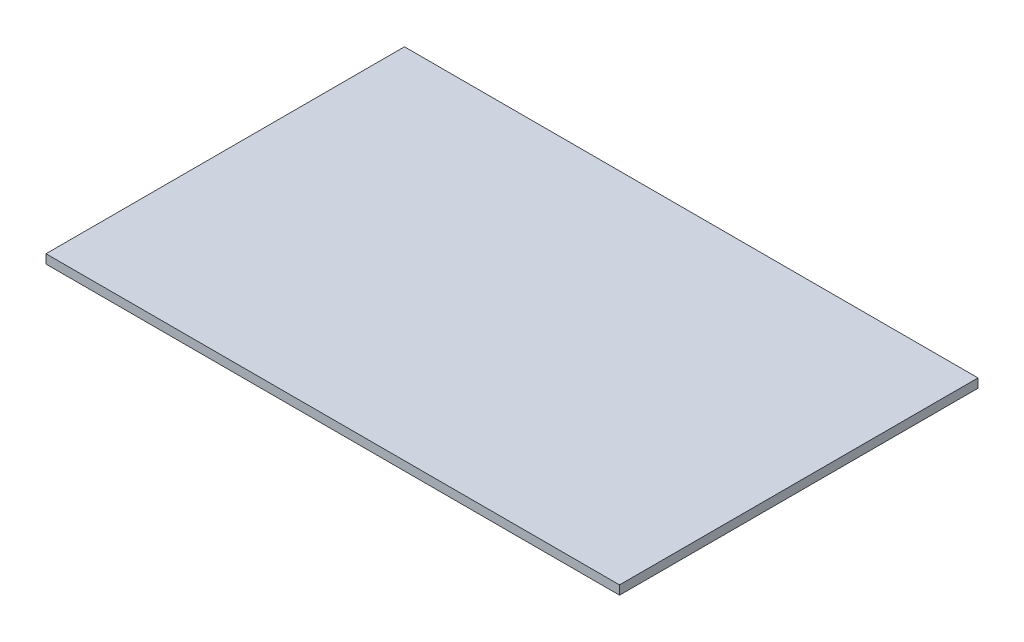
SolidWorks part; units mm, degrees
material "Beech"
ref_plane "Front Plane" through (0, 0, 0) normal (0, 0, 1) x (1, 0, 0)
ref_plane "Top Plane" through (0, 0, 0) normal (0, 1, 0) x (1, 0, 0)
ref_plane "Right Plane" through (0, 0, 0) normal (1, 0, 0) x (0, 0, -1)
sketch "Sketch1" plane through (0, 0, 0) normal (0, 1, 0) x (1, 0, 0)
  line L1 (-406.4, 254) -> (0, 254)
  line L2 (-406.4, 254) -> (-406.4, 0)
  line L3 (-406.4, 0) -> (0, 0)
  line L4 (0, 254) -> (0, 0)
  dimension "D1" = 406.4
  dimension "D2" = 254
extrude "Boss-Extrude1" add sketch "Sketch1" along normal blind 6.35
